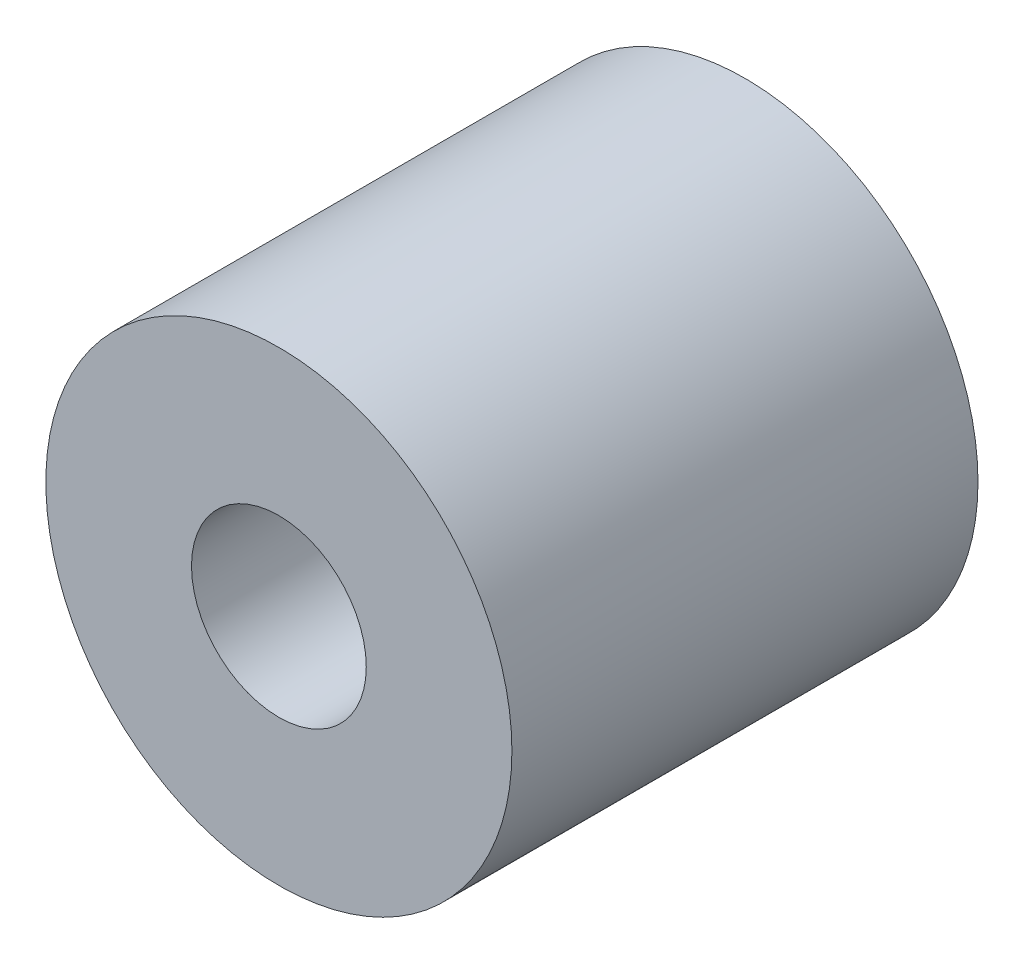
SolidWorks part; units mm, degrees
material "PBT General Purpose"
ref_plane "Front" through (0, 0, 0) normal (0, 0, 1) x (1, 0, 0)
ref_plane "Top" through (0, 0, 0) normal (0, 1, 0) x (1, 0, 0)
ref_plane "Right" through (0, 0, 0) normal (1, 0, 0) x (0, 0, -1)
sketch "Sketch1" plane through (0, 0, 0) normal (0, 0, 1) x (1, 0, 0)
  circle A0 centre (0, 0) radius 4
  circle A1 centre (0, 0) radius 1.5
  dimension "D1" = 8
  dimension "D2" = 3
extrude "Boss-Extrude1" add sketch "Sketch1" along normal blind 8
